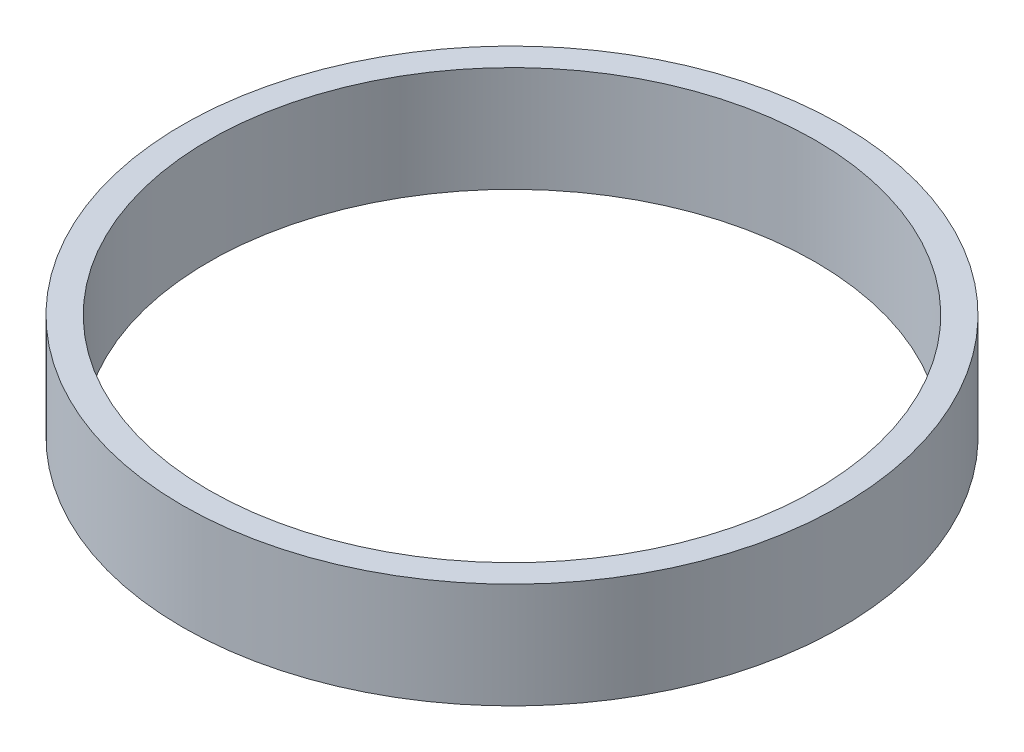
SolidWorks part; units mm, degrees
material "Silicon Rubber"
ref_plane "Front Plane" through (0, 0, 0) normal (0, 0, 1) x (1, 0, 0)
ref_plane "Top Plane" through (0, 0, 0) normal (0, 1, 0) x (1, 0, 0)
ref_plane "Right Plane" through (0, 0, 0) normal (1, 0, 0) x (0, 0, -1)
sketch "Sketch1" plane through (0, 0, 0) normal (0, 1, 0) x (1, 0, 0)
  circle A0 centre (0, 0) radius 5.75
  circle A1 centre (0, 0) radius 6.25
  dimension "D1" = 11.5
  dimension "D2" = 12.5
extrude "Boss-Extrude1" add sketch "Sketch1" along normal blind 2
